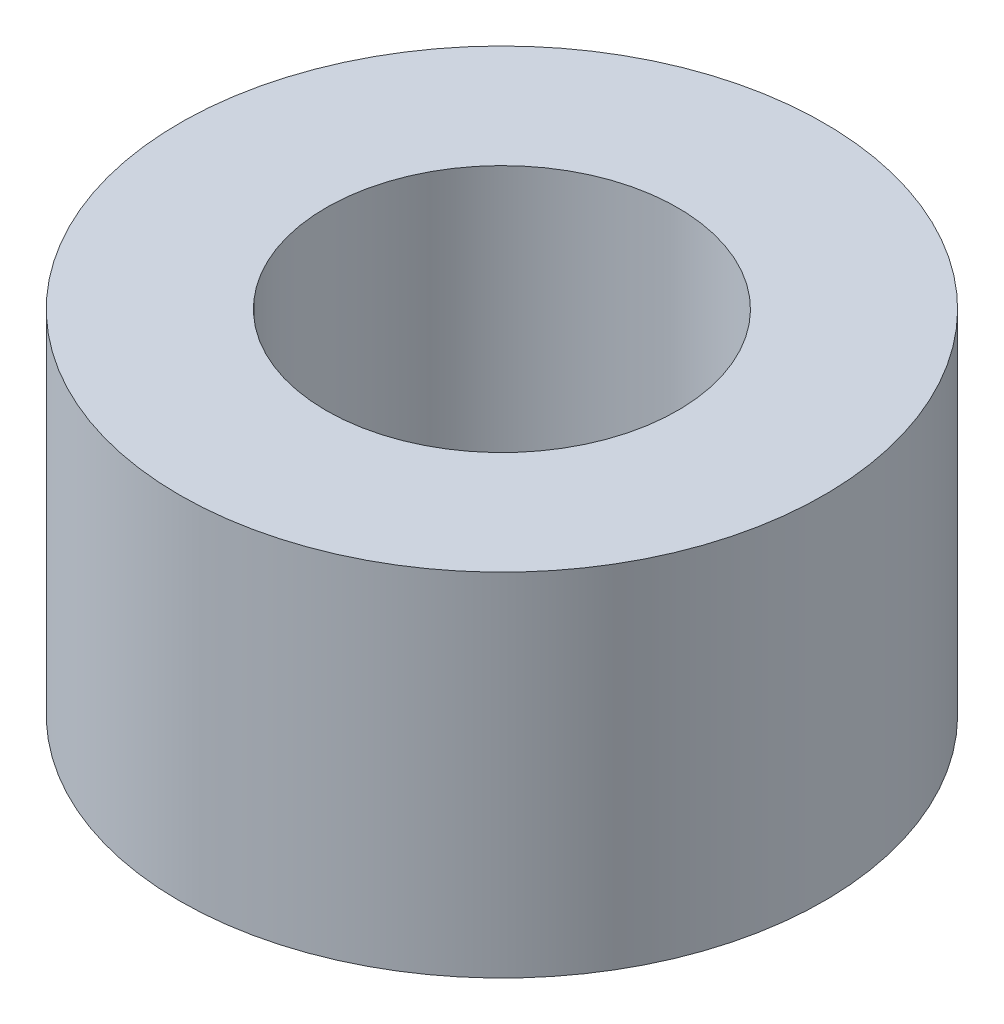
SolidWorks part; units mm, degrees
ref_plane "Front Plane" through (0, 0, 0) normal (0, 0, 1) x (1, 0, 0)
ref_plane "Top Plane" through (0, 0, 0) normal (0, 1, 0) x (1, 0, 0)
ref_plane "Right Plane" through (0, 0, 0) normal (1, 0, 0) x (0, 0, -1)
sketch "Sketch1" plane through (0, 0, 0) normal (0, 1, 0) x (1, 0, 0)
  circle A0 centre (0, 0) radius 3
  circle A1 centre (0, 0) radius 5.5
  dimension "D1" = 6
  dimension "D2" = 11
extrude "Boss-Extrude1" add sketch "Sketch1" along normal blind 6
